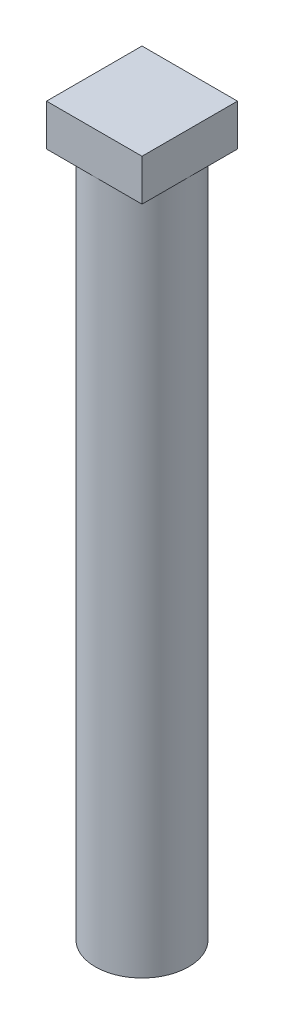
SolidWorks part; units mm, degrees
ref_plane "Front Plane" through (0, 0, 0) normal (0, 0, 1) x (1, 0, 0)
ref_plane "Top Plane" through (0, 0, 0) normal (0, 1, 0) x (1, 0, 0)
ref_plane "Right Plane" through (0, 0, 0) normal (1, 0, 0) x (0, 0, -1)
sketch "Sketch1" plane through (0, 0, 0) normal (0, 1, 0) x (1, 0, 0)
  circle A0 centre (0, 0) radius 2.25
  dimension "D1" = 4.5
extrude "Boss-Extrude1" add sketch "Sketch1" along normal blind 35
sketch "Sketch2" plane through (0, 35, 0) normal (0, 1, 0) x (1, 0, 0)
  line L1 (-2.3, -2.3) -> (2.3, -2.3)
  line L2 (-2.3, -2.3) -> (-2.3, 2.3)
  line L3 (-2.3, 2.3) -> (2.3, 2.3)
  line L4 (2.3, -2.3) -> (2.3, 2.3)
  line L5 (-2.3, -2.3) -> (2.3, 2.3) construction
  line L6 (-2.3, 2.3) -> (2.3, -2.3) construction
  point P0 (0, 0)
  dimension "D1" = 4.6
  dimension "D2" = 4.6
extrude "Boss-Extrude2" add sketch "Sketch2" against normal blind 2
